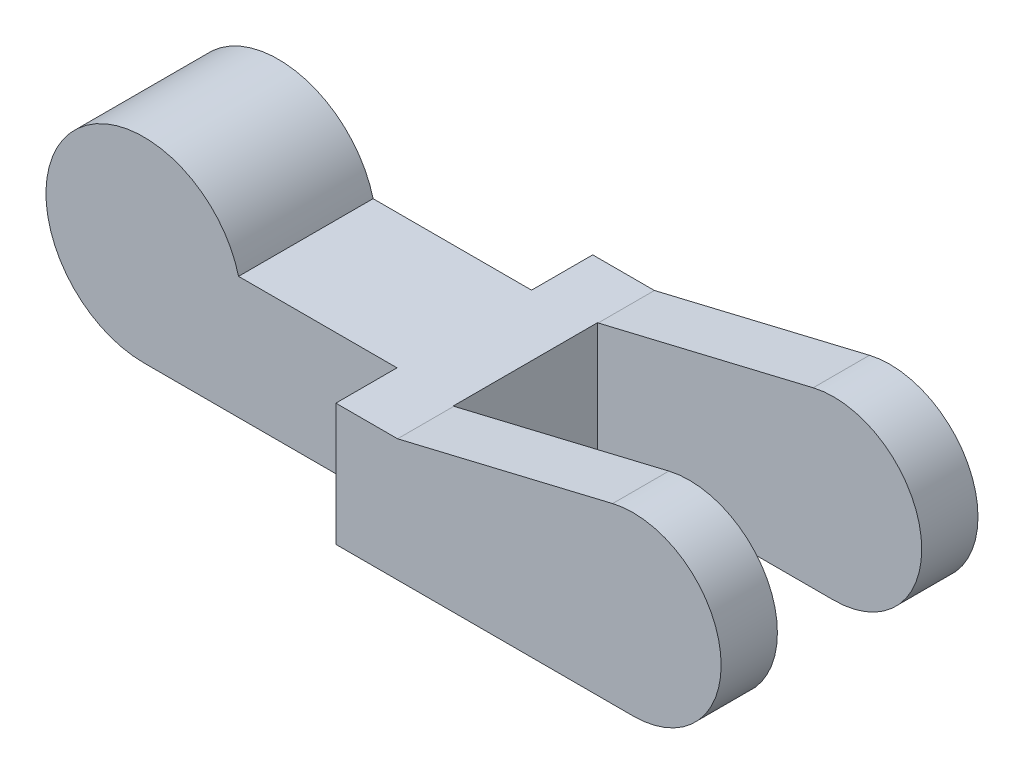
SolidWorks part; units mm, degrees
ref_plane "Front Plane" through (0, 0, 0) normal (0, 0, 1) x (1, 0, 0)
ref_plane "Top Plane" through (0, 0, 0) normal (0, 1, 0) x (1, 0, 0)
ref_plane "Right Plane" through (0, 0, 0) normal (1, 0, 0) x (0, 0, -1)
sketch "Sketch1" plane through (0, 0, 0) normal (0, 0, 1) x (1, 0, 0)
  line L0 (-80, 0) -> (-80, 450)
  line L1 (20, 77.4597) -> (20, 257.4597)
  line L2 (20, 257.4597) -> (62.0268, 433.2594)
  arc A0 (-80, 0) -> (20, 77.4597) centre (0, 0) ccw
  arc A1 (62.0268, 433.2594) -> (-80, 450) centre (-8, 450) ccw
  dimension "D1" = 160
  dimension "D3" = 144
  dimension "D2" = 450
  dimension "D4" = 100
  dimension "D5" = 180
extrude "Boss-Extrude1" add sketch "Sketch1" along normal mid plane 210
sketch "Sketch2" plane through (0, 0, 0) normal (1, 0, 0) x (0, 0, -1)
  line L0 (105, 522) -> (-105, 522) construction
  line L1 (-59, 558.6521) -> (59, 558.6521)
  line L2 (-59, 558.6521) -> (-59, 257)
  line L3 (-59, 257) -> (59, 257)
  line L4 (59, 558.6521) -> (59, 257)
  line L5 (-105, -80) -> (105, -80) construction
  line L6 (-118.2402, 207) -> (-55, 207)
  line L7 (-118.2402, 207) -> (-118.2402, -116.9621)
  line L8 (-118.2402, -116.9621) -> (-55, -116.9621)
  line L9 (-55, 207) -> (-55, -116.9621)
  line L10 (-105, 77.4597) -> (-105, 257.4597) construction
  line L11 (0, 617.7122) -> (0, -139.8912) construction
  line L12 (55, 207) -> (55, -116.9621)
  line L13 (118.2402, -116.9621) -> (55, -116.9621)
  line L14 (118.2402, 207) -> (118.2402, -116.9621)
  line L15 (118.2402, 207) -> (55, 207)
  point P6 (0, 257)
  dimension "D1" = 118
  dimension "D2" = 265
  dimension "D3" = 287
  dimension "D4" = 50
extrude "Cut-Extrude1" cut sketch "Sketch2" against normal through all both and the other way through all
sketch "Sketch3" plane through (0, 0, 0) normal (0, 0, 1) x (1, 0, 0)
  point P0 (-8, 450)
move or copy body "Body-Move/Copy1" bodies to move or copy 102 copy no translate (8, -450, 0) parameters "D1"=0, "D2"=0, "D3"=0
move or copy body "Body-Move/Copy2" bodies to move or copy 103 copy no rotation origin (0, 0, 0) rotation axis (0.7071, 0.7071, 0) rotation angle 180
sketch "Sketch4" plane through (0, 0, 0) normal (0, 0, 1) x (1, 0, 0)
  point P0 (-450, 8)
